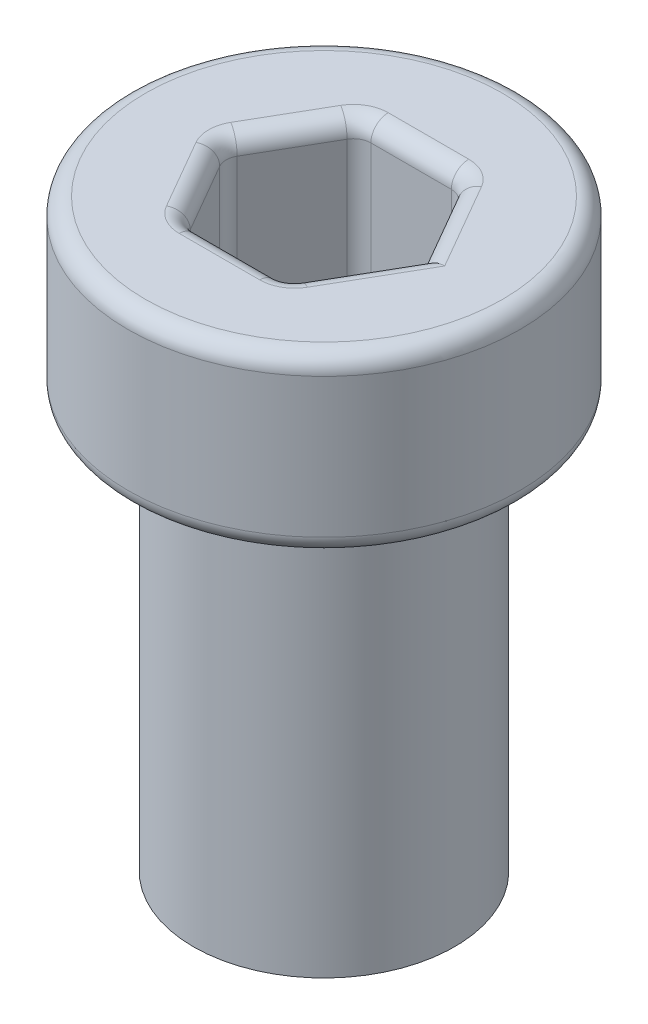
SolidWorks part; units mm, degrees
material "201 Annealed Stainless Steel (SS)"
ref_plane "Front Plane" through (0, 0, 0) normal (0, 0, 1) x (1, 0, 0)
ref_plane "Top Plane" through (0, 0, 0) normal (0, 1, 0) x (1, 0, 0)
ref_plane "Right Plane" through (0, 0, 0) normal (1, 0, 0) x (0, 0, -1)
sketch "Master Sketch" plane through (0, 0, 0) normal (0, 1, 0) x (1, 0, 0)
  line L1 (0.5774, 1) -> (-0.5774, 1)
  line L2 (-0.5774, 1) -> (-1.1547, 0)
  line L3 (-1.1547, 0) -> (-0.5774, -1)
  line L4 (-0.5774, -1) -> (0.5774, -1)
  line L5 (0.5774, -1) -> (1.1547, 0)
  line L6 (1.1547, 0) -> (0.5774, 1)
  circle A0 centre (0, 0) radius 2.25
  circle A1 centre (0, 0) radius 1 construction
  circle A2 centre (0, 0) radius 1.5
  dimension "D1" = 4.5
  dimension "D2" = 2
  dimension "D3" = 3
sketch "Head Sketch" plane through (0, 0, 0) normal (0, 1, 0) x (1, 0, 0)
  line L0 (-0.5774, 1) -> (-1.1547, 0) construction
  line L1 (-0.5774, 1) -> (-1.1547, 0)
  line L2 (-1.1547, 0) -> (-0.5774, -1) construction
  line L3 (-0.5774, -1) -> (0.5774, -1) construction
  line L4 (0.5774, -1) -> (1.1547, 0) construction
  line L5 (0.5774, 1) -> (-0.5774, 1) construction
  line L6 (1.1547, 0) -> (0.5774, 1) construction
  line L7 (-1.1547, 0) -> (-0.5774, -1)
  line L8 (-0.5774, -1) -> (0.5774, -1)
  line L9 (0.5774, -1) -> (1.1547, 0)
  line L10 (0.5774, 1) -> (-0.5774, 1)
  line L11 (1.1547, 0) -> (0.5774, 1)
  circle A0 centre (0, 0) radius 2.25 construction
  circle A1 centre (0, 0) radius 2.25
extrude "Head" add sketch "Head Sketch" along normal blind 2
sketch "Threaded Section Stub Sketch" plane through (0, 0, 0) normal (0, 1, 0) x (1, 0, 0)
  circle A0 centre (0, 0) radius 1.5 construction
  circle A1 centre (0, 0) radius 1.5
extrude "Boss-Extrude2" add sketch "Threaded Section Stub Sketch" against normal blind 5
cosmetic thread "Cosmetic Thread1" parameters "D2"=2.439
chamfer "End Of Bolt chamfer" distance 0.5 angle 30 1 edges at (0, -5, 1.5)
fillet "Cosmetic Fillets" radius 0.2 19 edges at (-0.5774, 1, -1) (-1.1547, 1, 0) (-0.5774, 1, 1) (0.5774, 1, 1) (0.5774, 1, -1) (0, 0, -1) (0.866, 0, -0.5) (-0.866, 0, -0.5) (-0.866, 0, 0.5) (0.866, 0, 0.5) (0, 0, 1) (0.866, 2, -0.5) (0.866, 2, 0.5) (0, 2, -1) (0, 2, 1) (-0.866, 2, 0.5) (-0.866, 2, -0.5) (0, 0, 2.25) (0, 2, 2.25)
